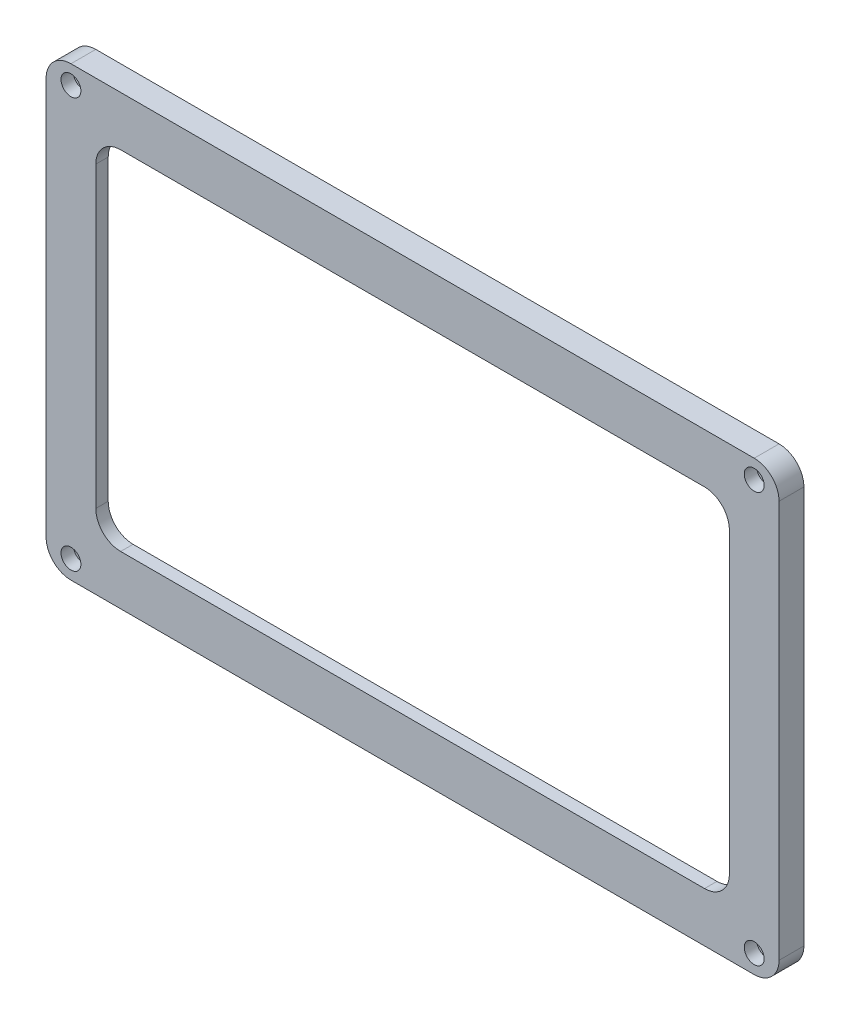
SolidWorks part; units mm, degrees
material "3.0205 (EN-AW 1200)"
ref_plane "前视基准面" through (0, 0, 0) normal (0, 0, 1) x (1, 0, 0)
ref_plane "上视基准面" through (0, 0, 0) normal (0, 1, 0) x (1, 0, 0)
ref_plane "右视基准面" through (0, 0, 0) normal (1, 0, 0) x (0, 0, -1)
sketch "草图1" plane through (0, 0, 0) normal (0, 0, 1) x (1, 0, 0)
  line L1 (-29.5, -18) -> (29.5, -18)
  line L2 (-29.5, -18) -> (-29.5, 18)
  line L3 (-29.5, 18) -> (29.5, 18)
  line L4 (29.5, -18) -> (29.5, 18)
  line L5 (-29.5, -18) -> (29.5, 18) construction
  line L6 (-29.5, 18) -> (29.5, -18) construction
  point P0 (0, 0)
  dimension "D1" = 59
  dimension "D2" = 36
extrude "凸台-拉伸1" add sketch "草图1" along normal blind 3
sketch "草图2" plane through (0, 0, 0) normal (0, 0, -1) x (-1, 0, 0)
  line L1 (-26.75, -15.25) -> (26.75, -15.25)
  line L2 (-26.75, -15.25) -> (-26.75, 15.25)
  line L3 (-26.75, 15.25) -> (26.75, 15.25)
  line L4 (26.75, -15.25) -> (26.75, 15.25)
  line L5 (-26.75, -15.25) -> (26.75, 15.25) construction
  line L6 (-26.75, 15.25) -> (26.75, -15.25) construction
  point P0 (0, 0)
  dimension "D1" = 53.5
  dimension "D2" = 30.5
extrude "切除-拉伸1" cut sketch "草图2" against normal blind 2
sketch "草图3" plane through (0, 0, 3) normal (0, 0, 1) x (1, 0, 0)
  line L1 (-25.5, -14) -> (25.5, -14)
  line L2 (-25.5, -14) -> (-25.5, 14)
  line L3 (-25.5, 14) -> (25.5, 14)
  line L4 (25.5, -14) -> (25.5, 14)
  line L5 (-25.5, -14) -> (25.5, 14) construction
  line L6 (-25.5, 14) -> (25.5, -14) construction
  point P0 (0, 0)
  dimension "D1" = 51
  dimension "D2" = 28
extrude "切除-拉伸2" cut sketch "草图3" against normal blind 2
fillet "圆角1" radius 2 8 edges at (-25.5, -14, 2.5) (25.5, -14, 2.5) (25.5, 14, 2.5) (-25.5, 14, 2.5) (-29.5, 18, 1.5) (29.5, 18, 1.5) (29.5, -18, 1.5) (-29.5, -18, 1.5)
sketch "草图4" plane through (0, 0, 0) normal (0, 0, -1) x (-1, 0, 0)
  line L1 (-32.0456, -18.0313) -> (32.0456, -18.0313)
  line L2 (-32.0456, -18.0313) -> (-32.0456, 18.0313)
  line L3 (-32.0456, 18.0313) -> (32.0456, 18.0313)
  line L4 (32.0456, -18.0313) -> (32.0456, 18.0313)
  line L5 (-32.0456, -18.0313) -> (32.0456, 18.0313) construction
  line L6 (-32.0456, 18.0313) -> (32.0456, -18.0313) construction
  point P0 (0, 0)
extrude "切除-拉伸3" cut sketch "草图4" against normal blind 1
fillet "圆角2" radius 0.2 4 edges at (26.75, 15.25, 1.5) (-26.75, 15.25, 1.5) (-26.75, -15.25, 1.5) (26.75, -15.25, 1.5)
sketch "草图5" plane through (0, 0, 3) normal (0, 0, 1) x (1, 0, 0)
  line L1 (-27.5, -16.5) -> (27.5, -16.5) construction
  line L2 (-27.5, -16.5) -> (-27.5, 16.5) construction
  line L3 (-27.5, 16.5) -> (27.5, 16.5) construction
  line L4 (27.5, -16.5) -> (27.5, 16.5) construction
  line L5 (-27.5, -16.5) -> (27.5, 16.5) construction
  line L6 (-27.5, 16.5) -> (27.5, -16.5) construction
  circle A0 centre (-27.5, 16.5) radius 0.8
  circle A1 centre (27.5, 16.5) radius 0.8
  circle A2 centre (27.5, -16.5) radius 0.8
  circle A3 centre (-27.5, -16.5) radius 0.8
  point P0 (0, 0)
  dimension "D3" = 1.6
  dimension "D1" = 55
  dimension "D2" = 33
extrude "切除-拉伸4" cut sketch "草图5" against normal blind 1
sketch "草图6" plane through (0, 0, 2) normal (0, 0, 1) x (1, 0, 0)
  circle A0 centre (-27.5, 16.5) radius 0.6
  circle A1 centre (27.5, 16.5) radius 0.6
  circle A2 centre (27.5, -16.5) radius 0.6
  circle A3 centre (-27.5, -16.5) radius 0.6
  dimension "D1" = 1.2
extrude "切除-拉伸5" cut sketch "草图6" against normal blind 20.5
